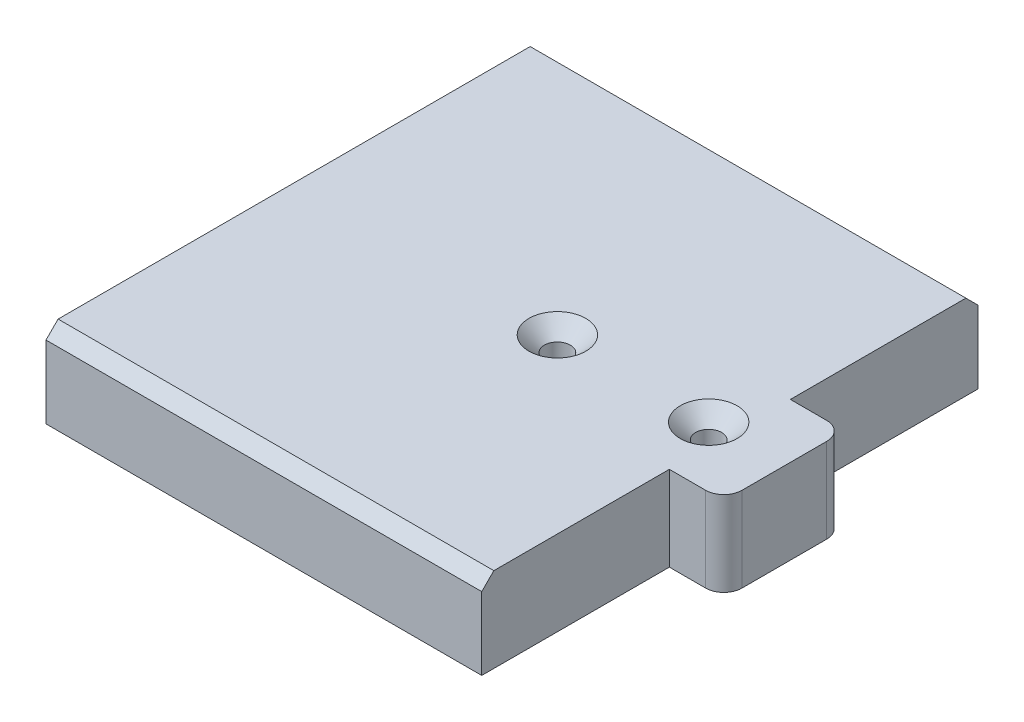
SolidWorks part; units mm, degrees
ref_plane "Plan de face" through (0, 0, 0) normal (0, 0, 1) x (1, 0, 0)
ref_plane "Plan de dessus" through (0, 0, 0) normal (0, 1, 0) x (1, 0, 0)
ref_plane "Plan de droite" through (0, 0, 0) normal (1, 0, 0) x (0, 0, -1)
sketch "Esquisse2" plane through (0, 0, 0) normal (0, 0, 1) x (1, 0, 0)
  line L1 (-36, -7) -> (36, -7)
  line L2 (-36, -7) -> (-36, 7)
  line L3 (-36, 7) -> (36, 7)
  line L4 (36, -7) -> (36, 7)
  line L5 (-36, -7) -> (36, 7) construction
  line L6 (-36, 7) -> (36, -7) construction
  point P0 (0, 0)
  dimension "D1" = 14
  dimension "D2" = 72
extrude "Boss.-Extru.1" add sketch "Esquisse2" along normal mid plane 82 contours L3 L4 L1 L2
sketch "Esquisse12" plane through (0, 7, 0) normal (0, 1, 0) x (1, 0, 0)
  line L0 (0, 0) -> (53.9301, 0) construction
  line L1 (45, 10) -> (45, -10)
  line L2 (45, -10) -> (36, -10)
  line L3 (36, -41) -> (36, 41) construction
  line L4 (36, -10) -> (36, 10)
  line L5 (45, 10) -> (36, 10)
  point P10 (36, 0)
  point P11 (45, 0)
  dimension "D1" = 20
  dimension "D2" = 9
extrude "Boss.-Extru.6" add sketch "Esquisse12" against normal up to surface (14 mm away) up to face at (0, -7, 0)
hole_wizard "Fraisage pour vis à tête fraisée M41" positions "Esquisse15" profile "Esquisse14" countersink size "M4" standard "Ansi Metric" end condition through all
sketch "Esquisse15" plane through (0, 7, 0) normal (0, 1, 0) x (1, 0, 0)
  line L0 (45, -10) -> (45, 10) construction
  point P0 (32.5, 0)
  point P2 (7.5, 0)
  point P8 (45, 0)
sketch "Esquisse14" plane through (32.5, 7, 0) normal (1, 0, 0) x (0, 0, 1)
  line L0 (0, 0) -> (0, 14)
  line L1 (0, 14) -> (2.15, 14)
  line L2 (2.15, 14) -> (2.15, 2.55)
  line L3 (2.15, 2.55) -> (4.7, 0)
  line L5 (4.7, 0) -> (0, 0)
  line L6 (-2.15, 2.55) -> (-4.7, 0) construction
  line L11 (0, -6.35) -> (0, 107.95) construction
  dimension "Diamètre du perçage jusqu'au prochain" = 4.3
  dimension "Profondeur du perçage jusqu'au prochain" = 14
  dimension "Diamètre du fraisage entrant" = 9.4
  dimension "Angle du fraisage entrant" = 90
sketch "Esquisse6" plane through (0, 0, -41) normal (0, 0, 1) x (1, 0, 0)
  line L0 (-36, -7) -> (36, -7) construction
  line L1 (-28, -7) -> (-8, -7)
  line L2 (-28, -7) -> (-28, 3)
  line L3 (-28, 3) -> (-8, 3)
  line L4 (-8, -7) -> (-8, 3)
  line L8 (-36, -7) -> (-36, 7) construction
  line L9 (-36, 7) -> (36, 7) construction
  dimension "D1" = 8
  dimension "D2" = 20
  dimension "D3" = 4
extrude "Enlèv. mat.-Extru.3" cut sketch "Esquisse6" along normal up to next
sketch "Esquisse5" plane through (0, -7, 0) normal (0, 1, 0) x (1, 0, 0)
  line L0 (-36, -41) -> (-36, 41) construction
  line L1 (-36, 25) -> (-30.5, 25)
  line L2 (-36, 25) -> (-36, -25)
  line L3 (-36, -25) -> (-30.5, -25)
  line L4 (-30.5, 25) -> (-30.5, -25)
  point P6 (-30.5, 0)
  dimension "D1" = 5.5
  dimension "D2" = 50
extrude "Enlèv. mat.-Extru.2" cut sketch "Esquisse5" along normal blind 7
chamfer "Chanfrein1" distance 2 angle 45 2 edges at (0, 7, -41) (0, 7, 41)
sketch "Esquisse16" plane through (0, 3, 0) normal (0, -1, 0) x (1, 0, 0)
  line L0 (-28, -41) -> (-8, -41)
  line L1 (-28, -41) -> (-28, -34)
  line L2 (-8, -41) -> (-8, -34)
  line L3 (-28, -34) -> (-8, -34)
  dimension "D1" = 7
extrude "Boss.-Extru.7" add sketch "Esquisse16" along normal up to surface (10 mm away) up to face at (7.5, -7, 2.15)
mirror "Symétrie1" about plane through (0, 0, 0) normal (0, 0, 1) of "Boss.-Extru.7"
fillet "Congé1" radius 3 2 edges at (45, 0, -10) (45, 0, 10)
